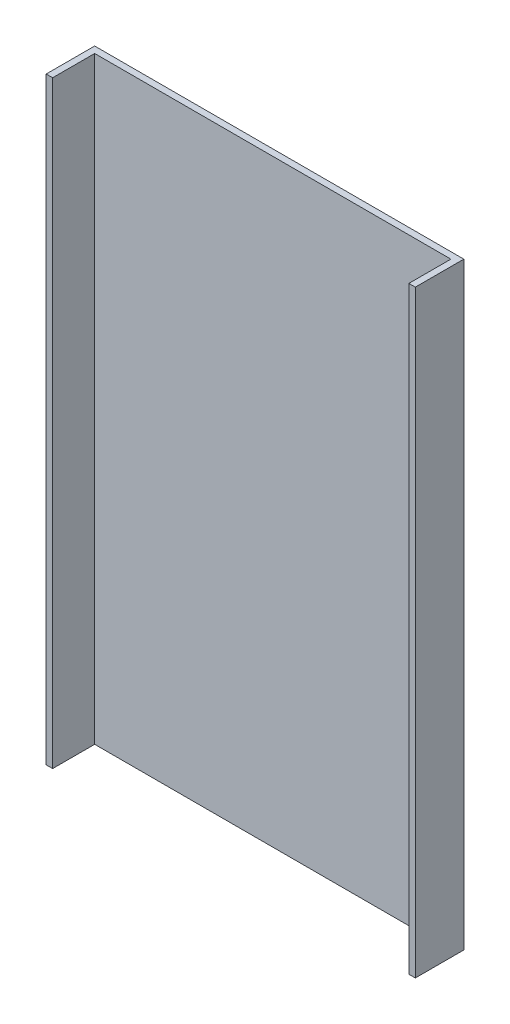
SolidWorks part; units mm, degrees
ref_plane "Front Plane" through (0, 0, 0) normal (0, 0, 1) x (1, 0, 0)
ref_plane "Top Plane" through (0, 0, 0) normal (0, 1, 0) x (1, 0, 0)
ref_plane "Right Plane" through (0, 0, 0) normal (1, 0, 0) x (0, 0, -1)
sketch "Sketch1" plane through (0, 0, 0) normal (0, 0, 1) x (1, 0, 0)
  line L1 (0, 0) -> (72.46, 0)
  line L2 (0, 0) -> (0, 117.44)
  line L3 (0, 117.44) -> (72.46, 117.44)
  line L4 (72.46, 0) -> (72.46, 117.44)
  dimension "D1" = 72.46
  dimension "D2" = 117.44
extrude "Boss-Extrude1" add sketch "Sketch1" along normal blind 1.27
sketch "Sketch2" plane through (0, 0, 1.27) normal (0, 0, 1) x (1, 0, 0)
  line L0 (0, 0) -> (72.46, 0) construction
  line L1 (0, 117.44) -> (1.27, 117.44)
  line L2 (0, 117.44) -> (0, 0)
  line L3 (0, 0) -> (1.27, 0)
  line L4 (1.27, 117.44) -> (1.27, 0)
  line L5 (72.46, 117.44) -> (0, 117.44) construction
  line L6 (72.46, 0) -> (71.19, 0)
  line L7 (72.46, 0) -> (72.46, 117.44)
  line L8 (72.46, 117.44) -> (71.19, 117.44)
  line L9 (71.19, 0) -> (71.19, 117.44)
  dimension "D1" = 1.27
  dimension "D2" = 1.27
extrude "Boss-Extrude2" add sketch "Sketch2" along normal blind 8.25
